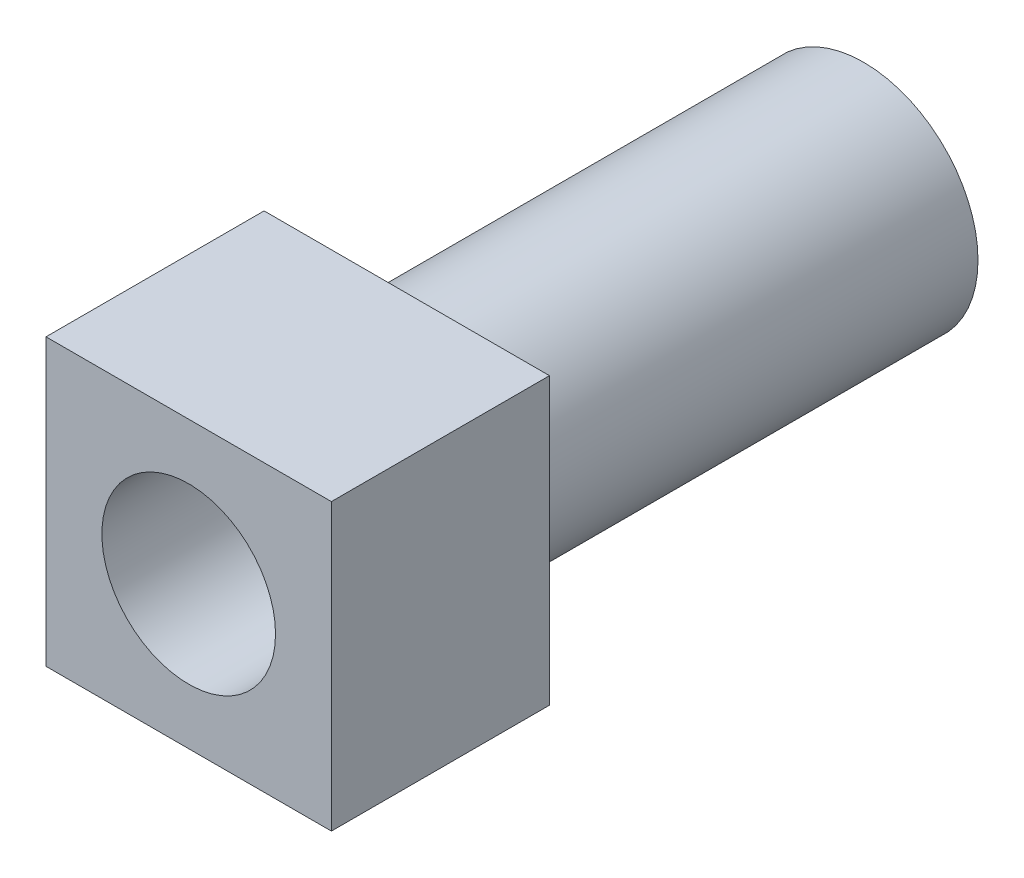
SolidWorks part; units mm, degrees
ref_plane "Plan de face" through (0, 0, 0) normal (0, 0, 1) x (1, 0, 0)
ref_plane "Plan de dessus" through (0, 0, 0) normal (0, 1, 0) x (1, 0, 0)
ref_plane "Plan de droite" through (0, 0, 0) normal (1, 0, 0) x (0, 0, -1)
sketch "Esquisse1" plane through (0, 0, 0) normal (0, 0, 1) x (1, 0, 0)
  line L1 (-37.0561, 15.4804) -> (-23.3161, 15.4804)
  line L2 (-37.0561, 15.4804) -> (-37.0561, 1.7404)
  line L3 (-37.0561, 1.7404) -> (-23.3161, 1.7404)
  line L4 (-23.3161, 15.4804) -> (-23.3161, 1.7404)
  dimension "D1" = 13.74
  dimension "D2" = 13.74
extrude "Boss.-Extru.1" add sketch "Esquisse1" along normal blind 10.5
sketch "Esquisse2" plane through (0, 0, 0) normal (0, 0, -1) x (-1, 0, 0)
  circle A1 centre (30.1861, 8.6104) radius 2.49
sketch "Esquisse3" plane through (0, 0, 10.5) normal (0, 0, 1) x (1, 0, 0)
  circle A0 centre (-30.1861, 8.6104) radius 4.18
extrude "Enlèv. mat.-Extru.2" cut sketch "Esquisse3" against normal blind 10
extrude "Boss.-Extru.4" add sketch "Esquisse2" along normal blind 22
sketch "Esquisse5" plane through (0, 0, -22) normal (0, 0, -1) x (-1, 0, 0)
  line L0 (27.6961, 8.6104) -> (29.6258, 11.0365)
  circle A0 centre (30.1861, 8.6104) radius 2.49 construction
  arc A1 (27.6961, 8.6104) -> (29.6258, 11.0365) centre (30.1861, 8.6104) ccw
  spline S0 degree 1 poles (29.6258, 11.0365) (27.6961, 8.6104) knots 0 0 1 1
  circle M2 centre (30.1861, 8.6104) radius 2.49
  dimension "D1" = 3.1
extrude "Enlèv. mat.-Extru.4" cut sketch "Esquisse5" against normal blind 22 contours L0 M2
sketch "Esquisse6" plane through (0, 0, 0) normal (0, 0, -1) x (-1, 0, 0)
  circle A0 centre (30.1861, 8.6104) radius 5.5
  circle A2 centre (30.1861, 8.6104) radius 2.49
extrude "Boss.-Extru.5" add sketch "Esquisse6" along normal blind 22
